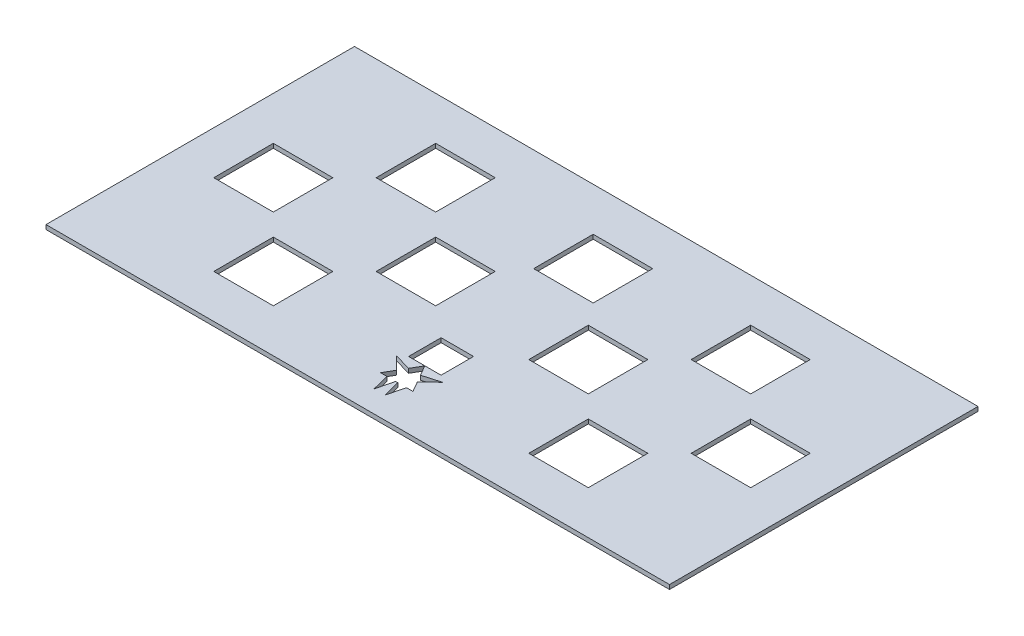
SolidWorks part; units mm, degrees
material "ABS"
ref_plane "Front Plane" through (0, 0, 0) normal (0, 0, 1) x (1, 0, 0)
ref_plane "Top Plane" through (0, 0, 0) normal (0, 1, 0) x (1, 0, 0)
ref_plane "Right Plane" through (0, 0, 0) normal (1, 0, 0) x (0, 0, -1)
sketch "Sketch1" plane through (0, 0, 0) normal (0, 1, 0) x (1, 0, 0)
  line L1 (-72, -35.625) -> (72, -35.625)
  line L2 (-72, -35.625) -> (-72, 35.625)
  line L3 (-72, 35.625) -> (72, 35.625)
  line L4 (72, -35.625) -> (72, 35.625)
  line L5 (-72, -35.625) -> (72, 35.625) construction
  line L6 (-72, 35.625) -> (72, -35.625) construction
  point P0 (0, 0)
  dimension "D1" = 144
  dimension "D2" = 71.25
extrude "Boss-Extrude1" add sketch "Sketch1" along normal blind 1
sketch "Sketch2" plane through (0, 1, 0) normal (0, 1, 0) x (1, 0, 0)
  line L0 (0, -35.625) -> (0, 35.625) construction
  line L1 (-43.25, 11.875) -> (-29.5, 11.875)
  line L2 (-43.25, 11.875) -> (-43.25, 25.625)
  line L3 (-43.25, 25.625) -> (-29.5, 25.625)
  line L4 (-29.5, 11.875) -> (-29.5, 25.625)
  line L5 (72, 35.625) -> (-72, 35.625) construction
  line L6 (-72, 35.625) -> (-72, -35.625) construction
  line L7 (-62, -6.875) -> (-48.25, -6.875)
  line L13 (-62, -6.875) -> (-62, 6.875)
  line L14 (-62, 6.875) -> (-48.25, 6.875)
  line L15 (-48.25, -6.875) -> (-48.25, 6.875)
  line L16 (-36.375, 11.875) -> (-36.375, -35.625) construction
  line L17 (-72, -35.625) -> (72, -35.625) construction
  line L18 (-48.25, 0) -> (0, 0) construction
  line L19 (-43.25, -11.875) -> (-29.5, -11.875)
  line L20 (-43.25, -11.875) -> (-43.25, -25.625)
  line L21 (-43.25, -25.625) -> (-29.5, -25.625)
  line L22 (-29.5, -11.875) -> (-29.5, -25.625)
  line L23 (-10.75, 6.875) -> (-24.5, 6.875)
  line L24 (-24.5, -6.875) -> (-24.5, 6.875)
  line L25 (-10.75, -6.875) -> (-24.5, -6.875)
  line L26 (-10.75, -6.875) -> (-10.75, 6.875)
  point P10 (0, 0)
  dimension "D1" = 13.75
  dimension "D2" = 10
  dimension "D3" = 10
  dimension "D4" = 5
  dimension "D5" = 5
extrude "Cut-Extrude1" cut sketch "Sketch2" against normal through all
mirror "Mirror1" about plane through (0, 0, 0) normal (1, 0, 0) of "Cut-Extrude1"
sketch "Sketch3" plane through (0, 1, 0) normal (0, 1, 0) x (1, 0, 0)
  line L0 (0, 0) -> (0, 35.625) construction
  line L1 (72, 35.625) -> (-72, 35.625) construction
  line L2 (-29.5, 11.875) -> (-29.5, 25.625) construction
  line L3 (-6.875, 11.875) -> (6.875, 11.875)
  line L4 (-6.875, 11.875) -> (-6.875, 25.625)
  line L5 (-6.875, 25.625) -> (6.875, 25.625)
  line L6 (6.875, 11.875) -> (6.875, 25.625)
  dimension "D1" = 10
extrude "Cut-Extrude2" cut sketch "Sketch3" against normal through all
sketch "Sketch4" plane through (0, 1, 0) normal (0, 1, 0) x (1, 0, 0)
  line L0 (0, 0) -> (0, -35.625) construction
  line L1 (-72, -35.625) -> (72, -35.625) construction
  line L2 (0, -20.1298) -> (-3.75, -26.625)
  line L3 (-3.75, -20.1298) -> (3.75, -20.1298)
  line L4 (-3.75, -20.1298) -> (-3.75, -12.6298)
  line L5 (-3.75, -12.6298) -> (3.75, -12.6298)
  line L6 (3.75, -20.1298) -> (3.75, -12.6298)
  line L7 (-3.75, -26.625) -> (3.75, -26.625)
  line L8 (3.75, -26.625) -> (0, -20.1298)
  line L9 (-2.25, -26.625) -> (-1.25, -30.625)
  line L10 (-1.25, -30.625) -> (-0.25, -26.625)
  line L11 (-1.25, -30.625) -> (-1.25, -26.625) construction
  line L12 (-2.375, -24.2434) -> (-5.3391, -21.3774)
  line L13 (-5.3391, -21.3774) -> (-1.375, -22.5114)
  line L14 (-5.3391, -21.3774) -> (-1.875, -23.3774) construction
  line L29 (5.3391, -21.3774) -> (1.375, -22.5114)
  line L30 (2.375, -24.2434) -> (5.3391, -21.3774)
  line L31 (2.25, -26.625) -> (1.25, -30.625)
  line L32 (1.25, -30.625) -> (0.25, -26.625)
  line L33 (-1.375, -22.5114) -> (-2.375, -24.2434)
  line L34 (2.375, -24.2434) -> (1.375, -22.5114)
  line L35 (2.25, -26.625) -> (0.25, -26.625)
  line L36 (-0.25, -26.625) -> (-2.25, -26.625)
  line L37 (-0.05, -20.1298) -> (-0.05, -20.2164)
  line L38 (0.05, -20.1298) -> (0.05, -20.2164)
  line L39 (-0.05, -20.2164) -> (0.05, -20.2164)
  line L40 (0.05, -20.1298) -> (-0.05, -20.1298)
  point P11 (0, -26.625)
  dimension "D1" = 7.5
  dimension "D2" = 2
  dimension "D3" = 7.5
  dimension "D4" = 2
  dimension "D5" = 1.5
  dimension "D6" = 4
  dimension "D7" = 5
  dimension "D8" = 0.1
extrude "Cut-Extrude6" cut sketch "Sketch4" against normal through all contours L3 L6 L5 L4 | L39 L2 L7 L8 | L8 L30 L29 | L13 L12 L2 | L9 L10 L7 | L32 L31 L7 | L3 L37 L2 | L38 L3 L8 | L2 L39 L8
